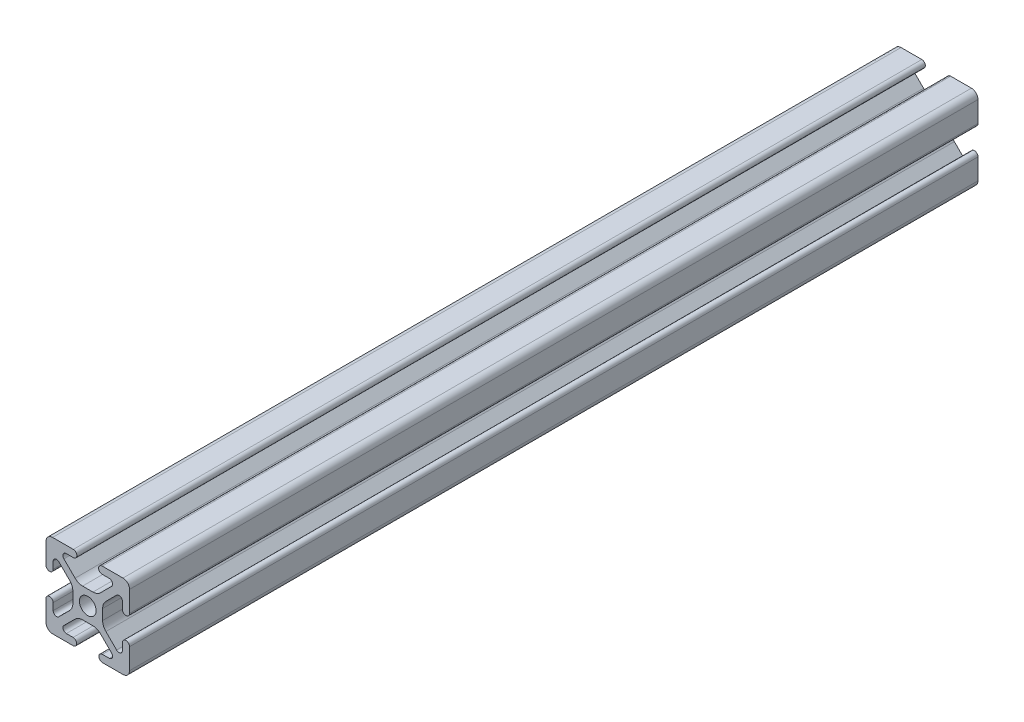
SolidWorks part; units mm, degrees
ref_plane "Front" through (0, 0, 0) normal (0, 0, 1) x (1, 0, 0)
ref_plane "Top" through (0, 0, 0) normal (0, 1, 0) x (1, 0, 0)
ref_plane "Right" through (0, 0, 0) normal (1, 0, 0) x (0, 0, -1)
ref_plane "Plane1" through (0, 0, -381) normal (0, 0, -1) x (-1, 0, 0)
sketch "Sketch1" plane through (0, 0, -381) normal (0, 0, -1) x (-1, 0, 0)
  line L0 (12.5, 4.32) -> (12.5, 10.5371)
  line L1 (10.5371, 12.5) -> (4.32, 12.5)
  line L2 (4.32, 10.36) -> (6.42, 10.36)
  line L3 (7.1337, 8.6353) -> (3.7953, 5.3018)
  line L4 (1.5554, 4.375) -> (-1.5554, 4.375)
  line L5 (-3.7953, 5.3018) -> (-7.1337, 8.6353)
  line L6 (-6.42, 10.36) -> (-4.32, 10.36)
  line L7 (-4.32, 12.5) -> (-10.5371, 12.5)
  line L8 (-12.5, 10.5371) -> (-12.5, 4.32)
  line L9 (-10.36, 4.32) -> (-10.36, 6.3969)
  line L10 (-8.6363, 7.1116) -> (-5.4322, 3.9121)
  line L11 (-4.455, 1.5554) -> (-4.455, -1.5554)
  line L12 (-5.4322, -3.9121) -> (-8.6363, -7.1116)
  line L13 (-10.36, -6.3969) -> (-10.36, -4.32)
  line L14 (-12.5, -4.32) -> (-12.5, -10.5371)
  line L15 (-10.5371, -12.5) -> (-4.3879, -12.5)
  line L16 (-4.3879, -10.36) -> (-6.42, -10.36)
  line L17 (-7.1337, -8.6353) -> (-3.7953, -5.3018)
  line L18 (-1.5554, -4.375) -> (1.5554, -4.375)
  line L19 (3.7953, -5.3018) -> (7.1337, -8.6353)
  line L20 (6.42, -10.36) -> (4.3879, -10.36)
  line L21 (4.3879, -12.5) -> (10.5371, -12.5)
  line L22 (12.5, -10.5371) -> (12.5, -4.32)
  line L23 (10.36, -4.32) -> (10.36, -6.3969)
  line L24 (8.6363, -7.1116) -> (5.4322, -3.9121)
  line L25 (4.455, -1.5554) -> (4.455, 1.5554)
  line L26 (5.4322, 3.9121) -> (8.6363, 7.1116)
  line L27 (10.36, 6.3969) -> (10.36, 4.32)
  circle A0 centre (0, 0) radius 2.5
  arc A1 (12.5, 10.5371) -> (10.5371, 12.5) centre (10.5371, 10.5371) ccw
  arc A2 (4.32, 12.5) -> (4.32, 10.36) centre (4.32, 11.43) ccw
  arc A3 (6.42, 10.36) -> (7.1337, 8.6353) centre (6.42, 9.35) cw
  arc A4 (3.7953, 5.3018) -> (1.5554, 4.375) centre (1.5554, 7.545) cw
  arc A5 (-1.5554, 4.375) -> (-3.7953, 5.3018) centre (-1.5554, 7.545) cw
  arc A6 (-7.1337, 8.6353) -> (-6.42, 10.36) centre (-6.42, 9.35) cw
  arc A7 (-4.32, 10.36) -> (-4.32, 12.5) centre (-4.32, 11.43) ccw
  arc A8 (-10.5371, 12.5) -> (-12.5, 10.5371) centre (-10.5371, 10.5371) ccw
  arc A9 (-12.5, 4.32) -> (-10.36, 4.32) centre (-11.43, 4.32) ccw
  arc A10 (-10.36, 6.3969) -> (-8.6363, 7.1116) centre (-9.35, 6.3969) cw
  arc A11 (-5.4322, 3.9121) -> (-4.455, 1.5554) centre (-7.7855, 1.5554) cw
  arc A12 (-4.455, -1.5554) -> (-5.4322, -3.9121) centre (-7.7855, -1.5554) cw
  arc A13 (-8.6363, -7.1116) -> (-10.36, -6.3969) centre (-9.35, -6.3969) cw
  arc A14 (-10.36, -4.32) -> (-12.5, -4.32) centre (-11.43, -4.32) ccw
  arc A15 (-12.5, -10.5371) -> (-10.5371, -12.5) centre (-10.5371, -10.5371) ccw
  arc A16 (-4.3879, -12.5) -> (-4.3879, -10.36) centre (-4.3879, -11.43) ccw
  arc A17 (-6.42, -10.36) -> (-7.1337, -8.6353) centre (-6.42, -9.35) cw
  arc A18 (-3.7953, -5.3018) -> (-1.5554, -4.375) centre (-1.5554, -7.545) cw
  arc A19 (1.5554, -4.375) -> (3.7953, -5.3018) centre (1.5554, -7.545) cw
  arc A20 (7.1337, -8.6353) -> (6.42, -10.36) centre (6.42, -9.35) cw
  arc A21 (4.3879, -10.36) -> (4.3879, -12.5) centre (4.3879, -11.43) ccw
  arc A22 (10.5371, -12.5) -> (12.5, -10.5371) centre (10.5371, -10.5371) ccw
  arc A23 (12.5, -4.32) -> (10.36, -4.32) centre (11.43, -4.32) ccw
  arc A24 (10.36, -6.3969) -> (8.6363, -7.1116) centre (9.35, -6.3969) cw
  arc A25 (5.4322, -3.9121) -> (4.455, -1.5554) centre (7.7855, -1.5554) cw
  arc A26 (4.455, 1.5554) -> (5.4322, 3.9121) centre (7.7855, 1.5554) cw
  arc A27 (8.6363, 7.1116) -> (10.36, 6.3969) centre (9.35, 6.3969) cw
  arc A28 (10.36, 4.32) -> (12.5, 4.32) centre (11.43, 4.32) ccw
  dimension "D1" = 5
  dimension "D2" = 1.9629
  dimension "D3" = 1.07
  dimension "D4" = 1.01
  dimension "D5" = 3.17
  dimension "D6" = 3.3305
  dimension "D7" = 1.5554
  dimension "D8" = 3.7953
  dimension "D9" = 4.32
  dimension "D10" = 4.3879
  dimension "D11" = 4.455
  dimension "D12" = 1.5554
  dimension "D13" = 11.43
  dimension "D14" = 11.43
extrude "Boss-Extrude1" add sketch "Sketch1" against normal blind 254
